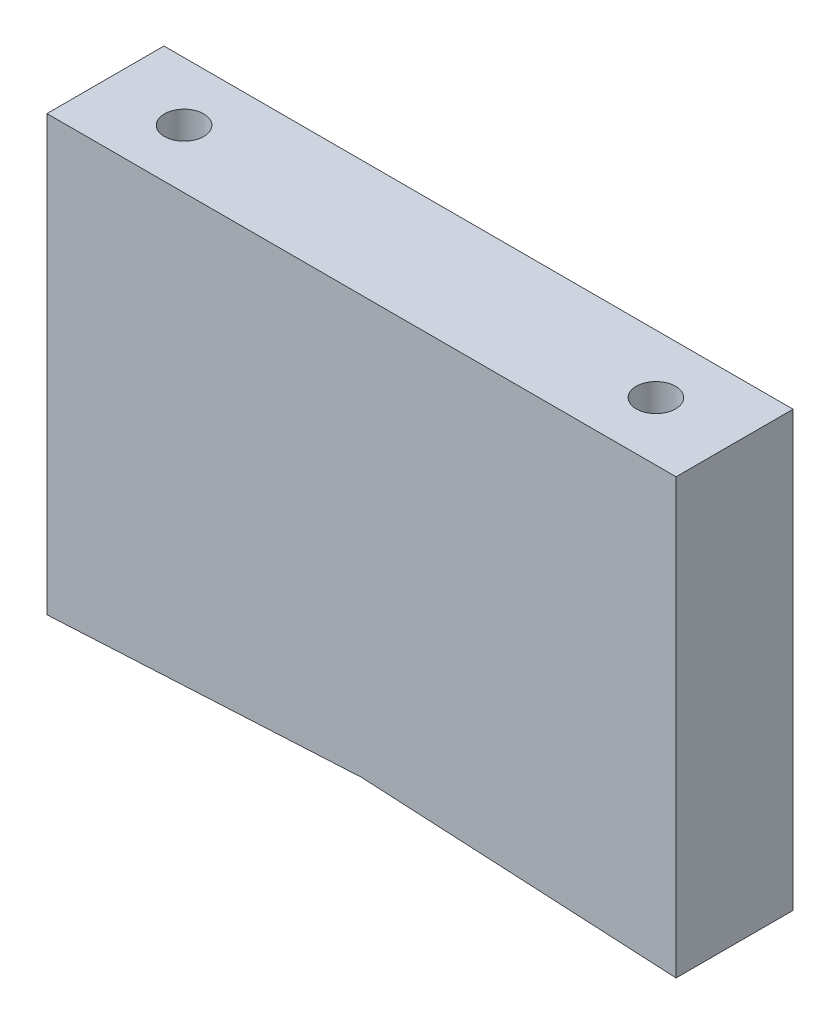
SolidWorks part; units mm, degrees
material "K110"
ref_plane "Front Plane" through (0, 0, 0) normal (0, 0, 1) x (1, 0, 0)
ref_plane "Top Plane" through (0, 0, 0) normal (0, 1, 0) x (1, 0, 0)
ref_plane "Right Plane" through (0, 0, 0) normal (1, 0, 0) x (0, 0, -1)
sketch "Sketch1" plane through (0, 0, 0) normal (0, 1, 0) x (1, 0, 0)
  line L1 (-40, -7.44) -> (40, -7.44)
  line L2 (-40, -7.44) -> (-40, 7.44)
  line L3 (-40, 7.44) -> (40, 7.44)
  line L4 (40, -7.44) -> (40, 7.44)
  line L5 (-40, -7.44) -> (40, 7.44) construction
  line L6 (-40, 7.44) -> (40, -7.44) construction
  point P0 (0, 0)
  dimension "D1" = 80
  dimension "D2" = 14.88
extrude "Boss-Extrude1" add sketch "Sketch1" against normal blind 55.2
sketch "Sketch3" plane through (0, 0, -7.44) normal (0, 0, -1) x (-1, 0, 0)
  line L0 (40, -55.2) -> (0, -53.1037)
  line L1 (0, -53.1037) -> (-40, -55.2)
  line L2 (-40, -55.2) -> (40, -55.2)
  dimension "D1" = 3
  dimension "D2" = 2.0963
extrude "Cut-Extrude1" cut sketch "Sketch3" against normal through all
hole_wizard "M6 Tapped Hole1" positions "Sketch9" profile "Sketch8" tap size "M6" standard "ISO"
sketch "Sketch9" plane through (0, 0, 0) normal (0, 1, 0) x (1, 0, 0)
  line L0 (0, 7.44) -> (0, -7.44) construction
  line L1 (40, 7.44) -> (-40, 7.44) construction
  line L2 (-40, -7.44) -> (40, -7.44) construction
  line L4 (-40, 7.44) -> (-40, -7.44) construction
  point P0 (-30, 0)
  point P2 (30, 0)
  dimension "D1" = 10
sketch "Sketch8" plane through (-30, 0, 0) normal (1, 0, 0) x (0, 0, 1)
  line L0 (0, 0) -> (0, 16.5022)
  line L1 (0, 16.5022) -> (2.5, 15)
  line L2 (2.5, 15) -> (2.5, 0)
  line L5 (2.5, 0) -> (0, 0)
  line L10 (0, 16.5022) -> (-2.5, 15) construction
  line L11 (0, -6.35) -> (0, 107.95) construction
  dimension "Tap Drill Dia." = 5
  dimension "Tap Drill Depth" = 15
  dimension "Drill Angle" = 118
cosmetic thread "Hole Thread1"
cosmetic thread "Hole Thread2"
